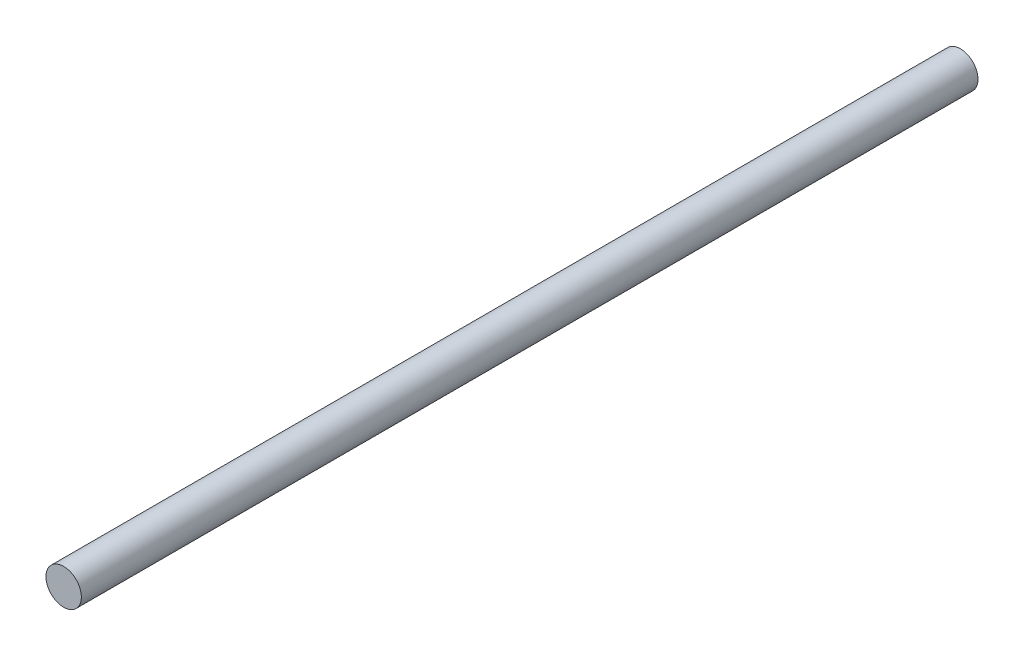
SolidWorks part; units mm, degrees
ref_plane "Plano frontal" through (0, 0, 0) normal (0, 0, 1) x (1, 0, 0)
ref_plane "Plano superior" through (0, 0, 0) normal (0, 1, 0) x (1, 0, 0)
ref_plane "Plano direito" through (0, 0, 0) normal (1, 0, 0) x (0, 0, -1)
sketch "Esboço1" plane through (0, 0, 0) normal (0, 0, 1) x (1, 0, 0)
  circle A0 centre (0, 0) radius 1.5
  dimension "D1" = 3
extrude "Ressalto-extrusão1" add sketch "Esboço1" along normal blind 76
